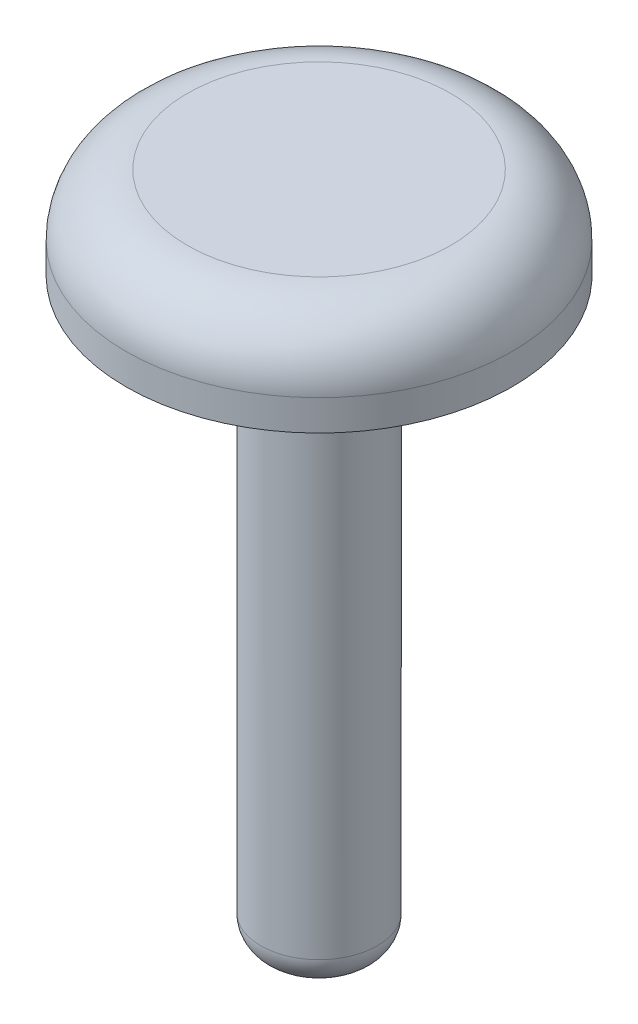
SolidWorks part; units mm, degrees
ref_plane "Alzado" through (0, 0, 0) normal (0, 0, 1) x (1, 0, 0)
ref_plane "Planta" through (0, 0, 0) normal (0, 1, 0) x (1, 0, 0)
ref_plane "Vista lateral" through (0, 0, 0) normal (1, 0, 0) x (0, 0, -1)
sketch "Croquis1" plane through (0, 0, 0) normal (0, 1, 0) x (1, 0, 0)
  circle A0 centre (0, 0) radius 0.95
extrude "Saliente-Extruir1" add sketch "Croquis1" along normal blind 11
sketch "Croquis2" plane through (0, 11, 0) normal (0, 1, 0) x (1, 0, 0)
  circle A0 centre (0, 0) radius 3.15
extrude "Saliente-Extruir2" add sketch "Croquis2" along normal blind 0.0001 and the other way blind 1.5
fillet "Redondeo3" radius 0.5 1 edges at (0, 0, 0.95)
fillet "Redondeo5" radius 1 1 edges at (0, 11.0001, 3.15)
sketch "Croquis4" plane through (0, 9.5, 0) normal (0, -1, 0) x (-1, 0, 0)
  circle A1 centre (0, 0) radius 2.65
  circle M2 centre (0, 0) radius 0.95
extrude "Cortar-Extruir4" cut sketch "Croquis4" against normal blind 1 contours A1 M2
